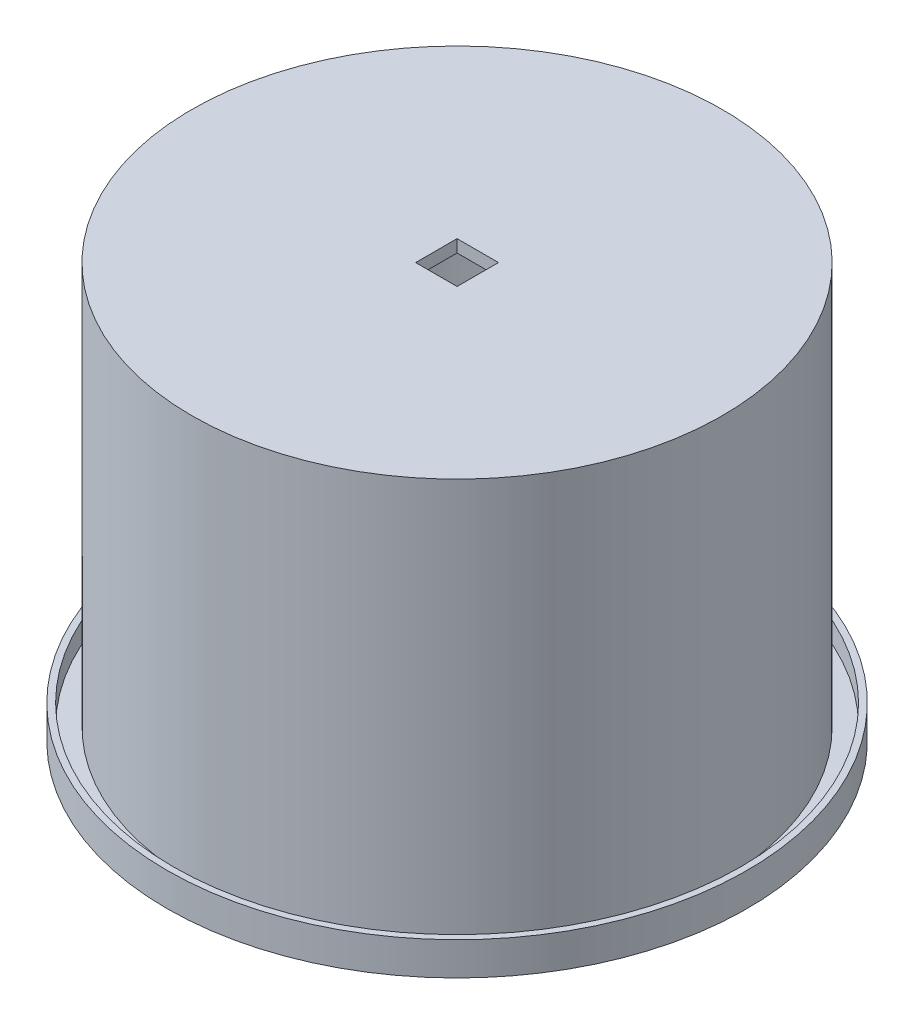
SolidWorks part; units mm, degrees
ref_plane "정면" through (0, 0, 0) normal (0, 0, 1) x (1, 0, 0)
ref_plane "윗면" through (0, 0, 0) normal (0, 1, 0) x (1, 0, 0)
ref_plane "우측면" through (0, 0, 0) normal (1, 0, 0) x (0, 0, -1)
sketch "스케치1" plane through (0, 0, 0) normal (0, 1, 0) x (1, 0, 0)
  circle A0 centre (0, 0) radius 70
  circle A1 centre (0, 0) radius 68.5
  dimension "D1" = 140
  dimension "D2" = 137
extrude "보스-돌출1" add sketch "스케치1" along normal blind 8
sketch "스케치2" plane through (0, 0, 0) normal (0, 1, 0) x (1, 0, 0)
  circle A0 centre (0, 0) radius 68.5
  circle A1 centre (0, 0) radius 64
  dimension "D1" = 137
  dimension "D2" = 128
extrude "보스-돌출2" add sketch "스케치2" along normal blind 3
sketch "스케치3" plane through (0, 0, 0) normal (0, 1, 0) x (1, 0, 0)
  circle A0 centre (0, 0) radius 62.5
  circle A1 centre (0, 0) radius 64
  dimension "D1" = 128
  dimension "D2" = 125
extrude "보스-돌출3" add sketch "스케치3" along normal blind 100
sketch "스케치4" plane through (0, 0, 0) normal (0, 1, 0) x (1, 0, 0)
  circle A0 centre (0, 0) radius 62.5
  dimension "D1" = 125
extrude "보스-돌출4" add sketch "스케치4" along normal blind 3 from offset 97
sketch "스케치5" plane through (0, 100, 0) normal (0, 1, 0) x (1, 0, 0)
  line L1 (-5, -5) -> (5, -5)
  line L2 (-5, -5) -> (-5, 5)
  line L3 (-5, 5) -> (5, 5)
  line L4 (5, -5) -> (5, 5)
  line L5 (-5, -5) -> (5, 5) construction
  line L6 (-5, 5) -> (5, -5) construction
  point P0 (0, 0)
  dimension "D1" = 10
  dimension "D2" = 10
extrude "컷-돌출1" cut sketch "스케치5" against normal blind 10
